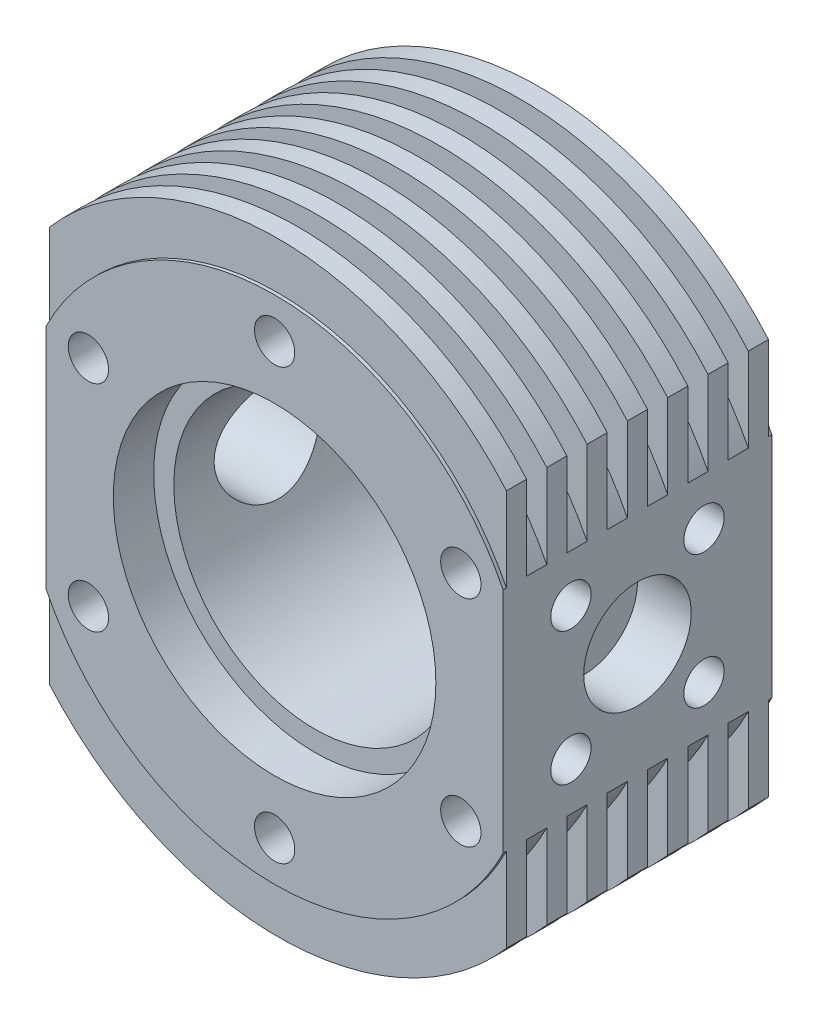
SolidWorks part; units mm, degrees
ref_plane "Front Plane" through (0, 0, 0) normal (0, 0, 1) x (1, 0, 0)
ref_plane "Top Plane" through (0, 0, 0) normal (0, 1, 0) x (1, 0, 0)
ref_plane "Right Plane" through (0, 0, 0) normal (1, 0, 0) x (0, 0, -1)
sketch "Sketch1" plane through (0, 0, 0) normal (0, 0, 1) x (1, 0, 0)
  line L2 (-17, -14.7394) -> (-17, 14.7394)
  line L4 (17, -14.7394) -> (17, 14.7394)
  circle A0 centre (0, 0) radius 10.5
  arc A1 (-17, -14.7394) -> (17, -14.7394) centre (0, 0) ccw
  arc A2 (17, 14.7394) -> (-17, 14.7394) centre (0, 0) ccw
  dimension "D1" = 21
  dimension "D2" = 45
  dimension "D3" = 17
  dimension "D4" = 17
extrude "Boss-Extrude1" add sketch "Sketch1" along normal blind 20
sketch "Sketch2" plane through (0, 0, 20) normal (0, 0, 1) x (1, 0, 0)
  circle A0 centre (0, 0) radius 12
  dimension "D1" = 24
extrude "Cut-Extrude1" cut sketch "Sketch2" against normal blind 3
sketch "Sketch3" plane through (0, 0, 0) normal (0, 0, -1) x (-1, 0, 0)
  circle A0 centre (0, 0) radius 19
  arc M2 (-17, -14.7394) -> (17, -14.7394) centre (0, 0) ccw
  line M3 (17, -14.7394) -> (17, 14.7394)
  arc M4 (17, 14.7394) -> (-17, 14.7394) centre (0, 0) ccw
  line M5 (-17, 14.7394) -> (-17, -14.7394)
  dimension "D1" = 38
extrude "Cut-Extrude2" cut sketch "Sketch3" against normal blind 0.25 contours A0 M3 M4 M5 | A0 M5 M2 M3
sketch "Sketch4" plane through (0, 0, 20) normal (0, 0, 1) x (1, 0, 0)
  circle A0 centre (0, 0) radius 19
  arc M3 (-17, -14.7394) -> (17, -14.7394) centre (0, 0) ccw
  line M4 (17, -14.7394) -> (17, 14.7394)
  arc M5 (17, 14.7394) -> (-17, 14.7394) centre (0, 0) ccw
  line M6 (-17, 14.7394) -> (-17, -14.7394)
  dimension "D1" = 38
extrude "Cut-Extrude3" cut sketch "Sketch4" against normal blind 0.25 contours A0 M4 M5 M6 | A0 M6 M3 M4
ref_plane "Plane1" through (0, 0, 18.25) normal (0, 0, 1) x (1, 0, 0)
sketch "Sketch5" plane through (0, 0, 18.25) normal (0, 0, 1) x (1, 0, 0)
  line L0 (17, 8.4853) -> (17, 14.7394) construction
  line L1 (-17, 14.7394) -> (-17, 8.4853) construction
  line L2 (17, 8.4853) -> (17, 14.7394)
  line L3 (-17, 14.7394) -> (-17, 8.4853)
  arc A0 (17, 8.4853) -> (-17, 8.4853) centre (0, 0) ccw construction
  arc A1 (17, 14.7394) -> (-17, 14.7394) centre (0, 0) ccw construction
  arc A2 (17, 8.4853) -> (-17, 8.4853) centre (0, 0) ccw
  arc A3 (17, 14.7394) -> (-17, 14.7394) centre (0, 0) ccw
extrude "Cut-Extrude4" cut sketch "Sketch5" against normal blind 1.5
pattern_linear "LPattern1" count 6 spacing 3 along (0, 0, -1) of "Cut-Extrude4"
mirror "Mirror1" about plane through (0, 0, 0) normal (0, 1, 0) of "LPattern1", "Cut-Extrude4"
sketch "Sketch6" plane through (-17, 0, 0) normal (-1, 0, 0) x (0, 0, 1)
  line L0 (20, 8.4853) -> (20, -8.4853) construction
  circle A0 centre (10, 0) radius 4
  dimension "D1" = 8
  dimension "D2" = 10
extrude "Cut-Extrude5" cut sketch "Sketch6" against normal up to next
sketch "Sketch8" plane through (-17, 0, 0) normal (-1, 0, 0) x (0, 0, 1)
  line L0 (10, 0) -> (3, 0) construction
  line L1 (10, 0) -> (5.0503, 4.9497) construction
  line L2 (14.9497, 4.9497) -> (5.0503, -4.9497) construction
  line L3 (10, 0) -> (14.9497, -4.9497) construction
  circle A0 centre (10, 0) radius 4 construction
  circle A1 centre (10, 0) radius 4
  circle A2 centre (10, 0) radius 7 construction
  circle A3 centre (5.0503, 4.9497) radius 1.5
  circle A4 centre (14.9497, 4.9497) radius 1.5
  circle A5 centre (14.9497, -4.9497) radius 1.5
  circle A6 centre (5.0503, -4.9497) radius 1.5
  point P16 (10, 0)
  dimension "D1" = 14
  dimension "D3" = 3
  dimension "D2" = 45
  dimension "D5" = 9.8995
  dimension "D4" = 4
extrude "Cut-Extrude6" cut sketch "Sketch8" against normal blind 4
ref_plane "Plane2" through (0, 0, 10) normal (0, 0, -1) x (-1, 0, 0)
sketch "Sketch9" plane through (0, 0, 10) normal (0, 0, -1) x (-1, 0, 0)
  line L0 (-17, 0) -> (-11.5, 0)
  line L1 (-17, -8.4853) -> (-17, 8.4853) construction
  line L2 (-11.5, 0) -> (-14.5, -3)
  line L3 (-14.5, -3) -> (-17, -3)
  line L4 (-17, -3) -> (-17, 0)
  dimension "D1" = 3
  dimension "D2" = 2.5
  dimension "D3" = 45
revolve "Cut-Revolve1" cut sketch "Sketch9" angle 360 about L0
mirror "Mirror2" about plane through (0, 0, 0) normal (1, 0, 0) of "Cut-Extrude6"
sketch "Sketch10" plane through (0, 0, 0) normal (0, 0, -1) x (-1, 0, 0)
  line L0 (0, 0) -> (13.8564, 8) construction
  line L1 (0, 0) -> (0, 16) construction
  circle A0 centre (0, 0) radius 16 construction
  circle A1 centre (0, 16) radius 1.5
  circle A2 centre (13.8564, 8) radius 1.5
  circle A3 centre (13.8564, -8) radius 1.5
  circle A4 centre (0, -16) radius 1.5
  circle A5 centre (-13.8564, -8) radius 1.5
  circle A6 centre (-13.8564, 8) radius 1.5
  point P18 (0, 0)
  dimension "D1" = 32
  dimension "D2" = 3
  dimension "D4" = 60
  dimension "D3" = 6
extrude "Cut-Extrude7" cut sketch "Sketch10" against normal blind 6
mirror "Mirror3" about plane through (0, 0, 10) normal (0, 0, -1) of "Cut-Extrude7"
